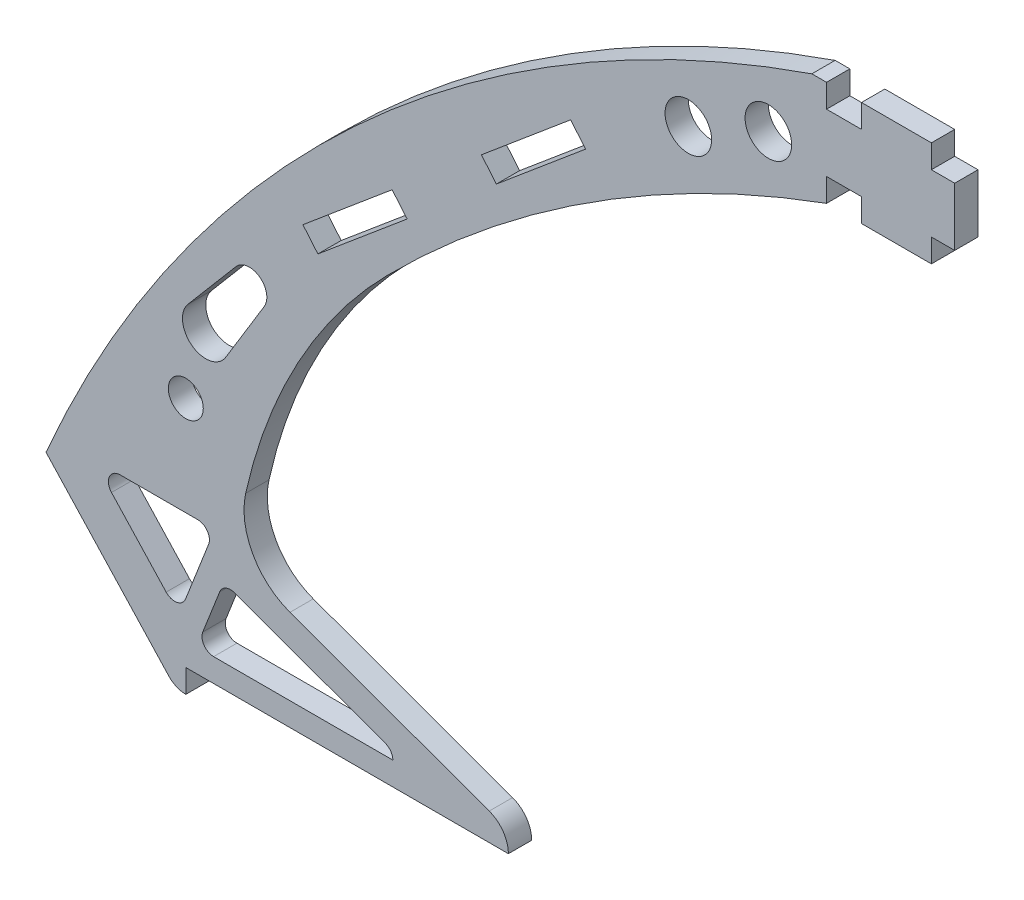
SolidWorks part; units mm, degrees
ref_plane "Front Plane" through (0, 0, 0) normal (0, 0, 1) x (1, 0, 0)
ref_plane "Top Plane" through (0, 0, 0) normal (0, 1, 0) x (1, 0, 0)
ref_plane "Right Plane" through (0, 0, 0) normal (1, 0, 0) x (0, 0, -1)
sketch "Sketch1" plane through (0, 0, 0) normal (0, 0, 1) x (1, 0, 0)
  line L0 (-62.3095, 0) -> (-90, 0)
  line L1 (-90, 0) -> (-90, -2)
  line L2 (-26, 71) -> (-32, 71)
  line L3 (-102, 10) -> (-91.4666, -1.3599)
  line L4 (0, -49.75) -> (0, 93.6118) construction
  line L5 (-35, 71) -> (-35, 69)
  line L6 (-32, 62) -> (-26, 62)
  line L7 (-32, 71) -> (-32, 69)
  line L8 (-35, 69) -> (-32, 69)
  line L9 (-35, 64) -> (-32, 64)
  line L10 (-26, 62) -> (-26, 64)
  line L11 (-26, 64) -> (-24, 64)
  line L12 (-24, 64) -> (-24, 69)
  line L13 (-24, 69) -> (-26, 69)
  line L14 (-32, 64) -> (-32, 62)
  line L15 (-26, 69) -> (-26, 71)
  line L16 (-35, 71) -> (-36.2629, 71)
  line L17 (-35, 64) -> (-35, 62)
  line L18 (-63.9545, 2.3492) -> (-81.0561, 8.5737)
  line L19 (-89.811, 27.0997) -> (-85.687, 31.9596)
  line L20 (-72.8863, 2.9397) -> (-85.8193, 7.6469)
  line L21 (0, -34) -> (-95.4491, 79.7518) construction
  line L22 (-64.8095, 0) -> (-81.9112, 6.2245) construction
  line L23 (-86.578, 24.7652) -> (-83.2622, 30.2088)
  line L24 (-95.6449, 11.5) -> (-88.9723, 11.5)
  line L25 (-78.662, 36.4098) -> (-71.0015, 42.8377)
  line L26 (-79.9475, 37.9419) -> (-72.2871, 44.3698)
  line L27 (-71.0015, 42.8377) -> (-72.2871, 44.3698)
  line L28 (-63.3411, 49.2656) -> (-64.6267, 50.7977)
  line L29 (-78.662, 36.4098) -> (-79.9475, 37.9419)
  line L30 (-55.6806, 55.6935) -> (-56.9662, 57.2255)
  line L31 (-63.3411, 49.2656) -> (-55.6806, 55.6935)
  line L32 (-96.3782, 9.8201) -> (-91.6861, 4.7599)
  line L33 (-87.6123, 2) -> (-72.2283, 2)
  line L34 (-88.041, 10.1355) -> (-90.0216, 5.0753)
  line L35 (-87.0925, 7.0717) -> (-88.5435, 3.3645)
  line L38 (-99.0669, 12.7197) -> (-88.5334, 1.3599) construction
  line L39 (-64.6267, 50.7977) -> (-56.9662, 57.2255)
  arc A0 (-91.4666, -1.3599) -> (-90, -2) centre (-90, 0) ccw
  arc A1 (-36.2629, 71) -> (-102, 10) centre (0, -34) ccw
  circle A2 centre (-90, 20) radius 1.5
  arc A3 (-35, 62) -> (-72.706, 37.7972) centre (0, -34) ccw
  arc A4 (-72.706, 37.7972) -> (-84.8597, 15.5198) centre (-40, 5.5) ccw
  arc A5 (-62.3095, 0) -> (-63.9545, 2.3492) centre (-64.8095, 0) ccw
  arc A6 (-84.8597, 15.5198) -> (-81.0561, 8.5737) centre (-79.004, 14.2119) ccw
  arc A7 (-34.8103, 66.7938) -> (-97.914, 8.2374) centre (0, -34) ccw construction
  circle A8 centre (-46.8645, 61.7855) radius 2
  circle A9 centre (-39.9939, 64.8516) radius 2
  arc A10 (-72.2283, 2) -> (-72.8863, 2.9397) centre (-73.2283, 2) ccw
  arc A11 (-96.3782, 9.8201) -> (-95.6449, 11.5) centre (-95.6449, 10.5) cw
  arc A12 (-88.041, 10.1355) -> (-88.9723, 11.5) centre (-88.9723, 10.5) ccw
  arc A13 (-91.6861, 4.7599) -> (-90.0216, 5.0753) centre (-90.9528, 5.4398) ccw
  arc A14 (-87.6123, 2) -> (-88.5435, 3.3645) centre (-87.6123, 3) cw
  arc A15 (-85.8193, 7.6469) -> (-87.0925, 7.0717) centre (-86.1613, 6.7072) ccw
  arc A16 (-89.811, 27.0997) -> (-86.578, 24.7652) centre (-88.286, 25.8056) ccw
  arc A17 (-83.2622, 30.2088) -> (-85.687, 31.9596) centre (-84.5432, 30.9891) ccw
  point P40 (-51.2554, 64.554)
  point P41 (-79.0608, 36.0752)
  point P42 (-97.8469, 16.5483)
  point P43 (-98.554, 17.2554)
  point P44 (-50.5483, 63.8469)
  point P45 (-99.2611, 17.9625)
  point P46 (-51.9625, 65.2611)
  point P48 (-79.7036, 36.8412)
  point P49 (-55.9246, 56.7942)
  point P50 (-55.2818, 56.0281)
  point P52 (-80.3464, 37.6072)
  point P53 (-56.5674, 57.5602)
  point P66 (-85.7909, 15.8843)
  point P67 (-92.3978, -0.9954)
  point P68 (-83.9285, 15.1553)
  point P69 (-90.5353, -1.7243)
  dimension "D1" = 4
  dimension "D2" = 5
  dimension "D3" = 6
  dimension "D5" = 8.9043
  dimension "D11" = 4
  dimension "D12" = 4
  dimension "D14" = 2
  dimension "D15" = 1
  dimension "D7" = 4
  dimension "D8" = 3
  dimension "D9" = 3
  dimension "D16" = 40
  dimension "D18" = 10
  dimension "D19" = 10
  dimension "D4" = 2.5
  dimension "D6" = 4.45
  dimension "D13" = 4
extrude "Boss-Extrude1" add sketch "Sketch1" along normal blind 2
